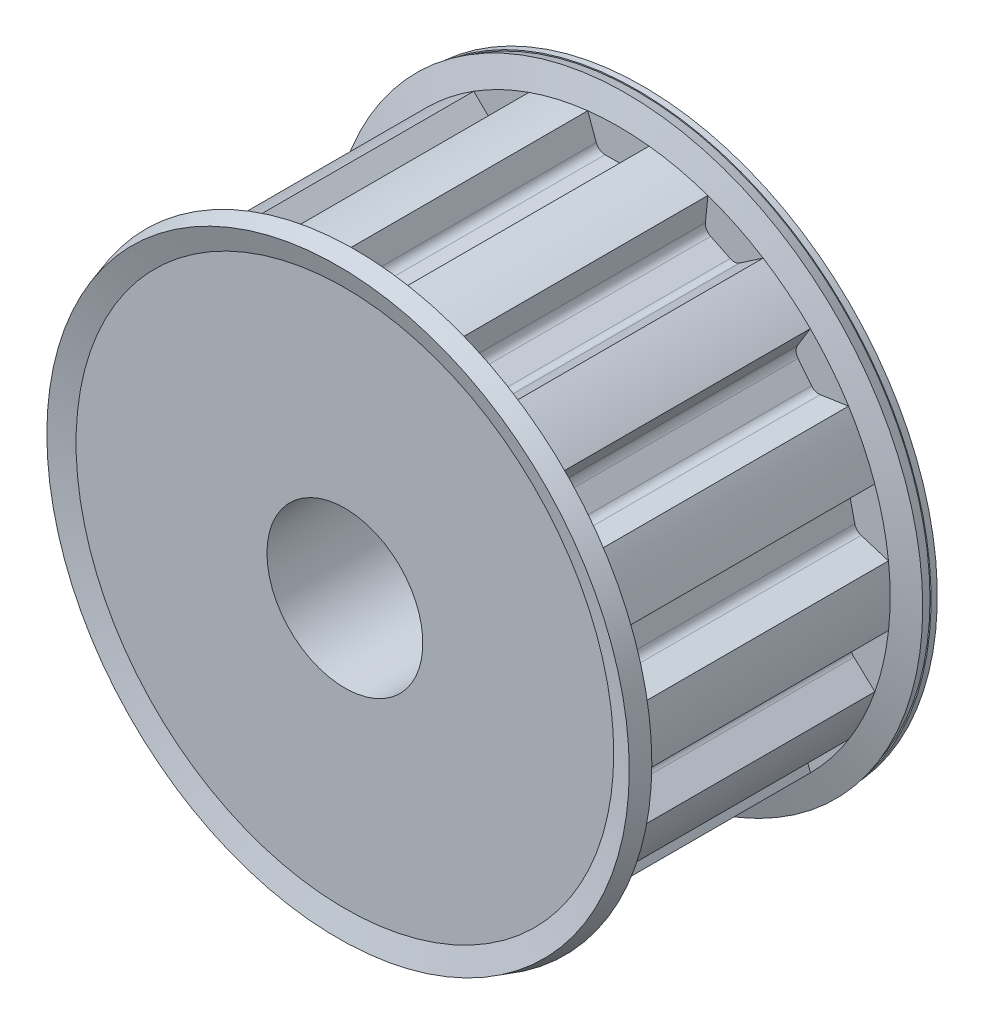
SolidWorks part; units mm, degrees
extrude "BasePulley" add sketch "Sketch1" against normal blind 10.414
sketch "Sketch1" plane through (0, 0, 0) normal (0, 0, 1) x (1, 0, 0)
  circle A0 centre (0, 0) radius 11.0617
  dimension "Outside_dia" = 22.1234
revolve "Flange" add sketch "Sketch2" angle 360 about L11
sketch "Sketch2" plane through (0, 0, 0) normal (1, 0, 0) x (0, 0, -1)
  line L0 (10.414, 11.0617) -> (10.7246, 12.0777)
  line L1 (10.7246, 12.0777) -> (11.429, 11.8623)
  line L2 (5.207, 0) -> (5.207, 66.675) construction
  line L3 (11.429, 11.8623) -> (11.1506, 10.9516)
  line L4 (11.1506, 10.9516) -> (11.1506, 0)
  line L5 (0, 11.0617) -> (-0.3106, 12.0777)
  line L6 (10.414, -11.0617) -> (10.414, 11.0617) construction
  line L7 (-0.3106, 12.0777) -> (-1.015, 11.8623)
  line L8 (-1.015, 11.8623) -> (-0.7366, 10.9516)
  line L9 (-0.7366, 10.9516) -> (-0.7366, 0)
  line L10 (10.414, 11.0617) -> (0, 11.0617)
  line L11 (0, 0) -> (38.2092, 0) construction
  line L12 (10.414, 0) -> (0, 0) construction
  line L13 (-0.7366, 0) -> (11.1506, 0)
  dimension "D1" = 5.207
  dimension "Flange_ang" = 17
  dimension "D3" = 0.7366
  dimension "D2" = 11.0617
  dimension "Flange_ht" = 1.016
material "ABS"
ref_plane "Plane1" through (0, 0, 0) normal (0, 0, 1) x (1, 0, 0)
ref_plane "Plane2" through (0, 0, 0) normal (0, 1, 0) x (1, 0, 0)
ref_plane "Plane3" through (0, 0, 0) normal (1, 0, 0) x (0, 0, -1)
other "Configuration Table"
sketch "Clipboard" plane through (0, 0, 0) normal (0, 0, 1) x (1, 0, 0)
  line L0 (0, 0) -> (6.604, 0)
  line L1 (0, 0) -> (9.8582, 2.4579)
  line L2 (0, 0) -> (9.8582, -2.4579)
  dimension "Num_grvs" = 14
ref_plane "Plane4" through (0, 0, -5.207) normal (0, 0, 1) x (1, 0, 0)
sketch "Sketch3" plane through (0, 0, -5.207) normal (0, 0, 1) x (1, 0, 0)
  line L0 (-1.2827, 11.0617) -> (-1.2827, 36.4617)
  line L1 (1.2827, 11.0617) -> (1.2827, 36.4617)
  line L2 (0, 0) -> (0, 11.0617) construction
  line L3 (-1.2827, 11.0617) -> (1.2827, 11.0617) construction
  line L4 (-0.5537, 9.7917) -> (0.3295, 9.7917)
  line L5 (1.2827, 11.0617) -> (0.6595, 9.9822)
  line L6 (-1.2827, 11.0617) -> (-0.9117, 10.0424)
  line L7 (1.2827, 36.4617) -> (-1.2827, 36.4617)
  arc A0 (0.3295, 9.7917) -> (0.6595, 9.9822) centre (0.3295, 10.1727) ccw
  arc A2 (-0.9117, 10.0424) -> (-0.5537, 9.7917) centre (-0.5537, 10.1727) ccw
  dimension "Grv_rad_bot" = 0.381
  dimension "Grv_ang" = 50
  dimension "D3" = 20
  dimension "Grv_width" = 2.5654
  dimension "D4" = 25.4
  dimension "D1" = 11.0617
  dimension "Grv_depth" = 1.27
extrude "Groove" cut sketch "Sketch3" against normal mid plane 10.414
pattern_circular "Grooves" count 14 every 25.714 about axis through (0, 0, -10.414) along (0, 0, 1) of "Groove"
sketch "Sketch4" plane through (0, 0, 0) normal (1, 0, 0) x (0, 0, -1)
  line L0 (0, 0) -> (47.6781, 0) construction
  line L1 (10.414, 0) -> (0, 0) construction
  line L2 (0, 0) -> (-0.254, 0)
  line L3 (-0.254, 0) -> (-0.254, 11.43)
  line L4 (-0.254, 11.43) -> (0, 11.43)
  line L5 (0, 11.43) -> (0, 0)
  line L6 (-0.254, -11.43) -> (0, -11.43) construction
revolve "BaseHub" add sketch "Sketch4" angle 360 about L0
sketch "BorSke" plane through (0, 0, -11.1506) normal (0, 0, -1) x (-1, 0, 0)
  circle A0 centre (0, 0) radius 3.175
extrude "Bore" cut sketch "BorSke" against normal through all
sketch "KeySke" plane through (0, 0, -11.1506) normal (0, 0, -1) x (-1, 0, 0)
  line L0 (0.127, 3.429) -> (0.127, 0)
  line L1 (0.127, 3.429) -> (-0.127, 3.429)
  line L2 (-0.127, 3.429) -> (-0.127, 0)
  line L3 (-0.127, 0) -> (0.127, 0)
  line L4 (0, 31.75) -> (0, -3.175) construction
  dimension "Width" = 10.414
extrude "Keyway" [suppressed] cut sketch "KeySke" against normal through all
pattern_circular "Keyway2" [suppressed] count 2 every 90
sketch "Sketch6" plane through (0, 0, -11.1506) normal (0, 0, 1) x (1, 0, 0)
  circle A0 centre (0, 0) radius 3.175
sketch "Sketch7" plane through (0, 0, -11.1506) normal (0, 0, -1) x (-1, 0, 0)
  circle A0 centre (0, 0) radius 11.9921
  circle A1 centre (0, 0) radius 3.175
extrude "Boss-Extrude1" add sketch "Sketch7" along normal blind 0.254
equation "\"D1@Plane4\" = \"Width@BasePulley\" / 2"
equation "\"D1@Groove\" = \"Width@BasePulley\""
equation "\"D1@Sketch3\" = \"Outside_dia@Sketch1\" / 2"
equation "\"D1@Sketch2\" = \"Width@BasePulley\" / 2"
equation "\"D2@Sketch2\" = \"Outside_dia@Sketch1\" / 2"
equation "\"D3@Sketch2\" = \"Flange_thickness@Sketch2\""
equation "\"Num_grvs@Clipboard\" = int( \"Num_grvs@Clipboard\" )"
equation "\"Show_grvs@Clipboard\" = int( \"Show_grvs@Clipboard\" )"
equation "\"Show_grvs@Clipboard\" = ((sgn( \"Show_grvs@Clipboard\" - \"Num_grvs@Clipboard\" )-1)*( \"Show_grvs@Clipboard\" - \"Num_grvs@Clipboard\" ))/-2+ \"Num_grvs@Clipboard\""
equation "\"Show_grvs@Clipboard\" = ((sgn( \"Show_grvs@Clipboard\" - 1.0)+1)*( \"Show_grvs@Clipboard\" - 1.0))/2 +1.0"
equation "\"Angle@Grooves\" = 360.0 / \"Num_grvs@Clipboard\""
equation "\"Num_grvs@Grooves\" =  \"Show_grvs@Clipboard\""
equation "\"Offset@KeySke\" = \"T_dim@Clipboard\" - \"Diameter@BorSke\" / 2.0"
equation "\"OAL@Clipboard\" = \"Overall_len@Clipboard\""
equation "\"Hub_depth@Sketch4\" = \"OAL@Clipboard\" - \"Width@BasePulley\""
